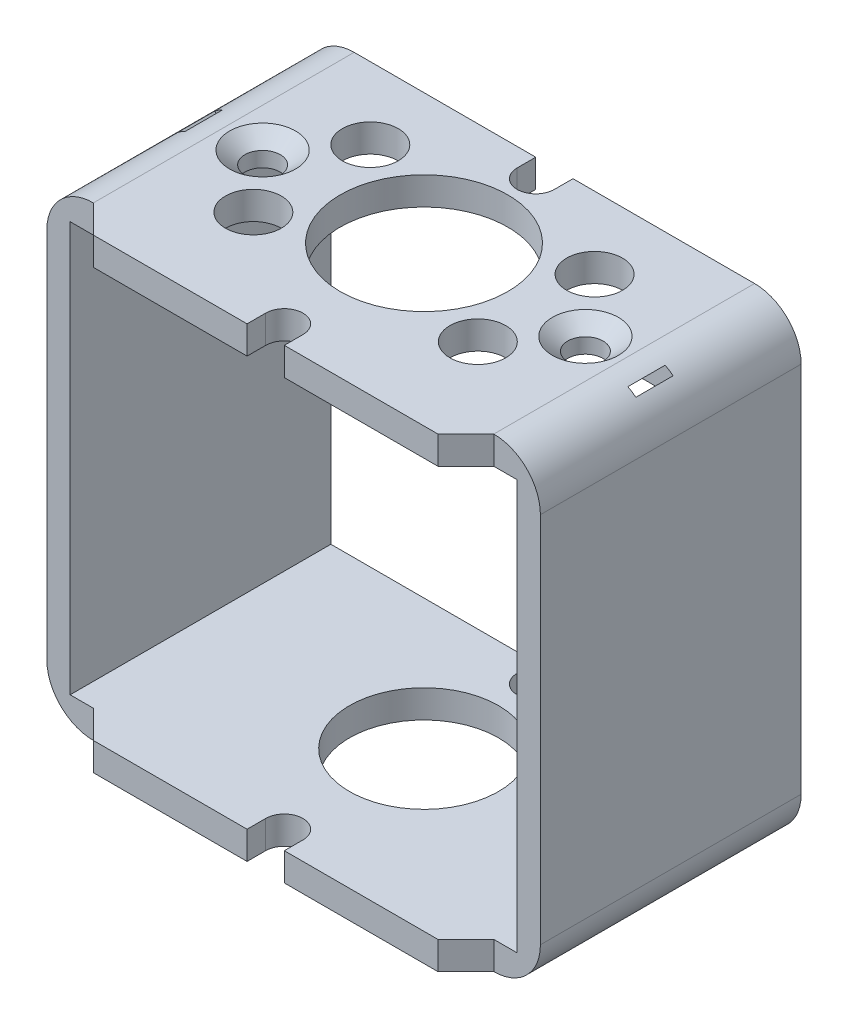
SolidWorks part; units mm, degrees
material "AISI 1020"
ref_plane "Front" through (0, 0, 0) normal (0, 0, 1) x (1, 0, 0)
ref_plane "Top" through (0, 0, 0) normal (0, 1, 0) x (1, 0, 0)
ref_plane "Right" through (0, 0, 0) normal (1, 0, 0) x (0, 0, -1)
sketch "Sketch1" plane through (0, 0, 0) normal (0, 0, 1) x (1, 0, 0)
  line L1 (-26.5, -25) -> (26.5, -25)
  line L2 (-26.5, -25) -> (-26.5, 25)
  line L3 (-26.5, 25) -> (26.5, 25)
  line L4 (26.5, -25) -> (26.5, 25)
  line L5 (-26.5, -25) -> (26.5, 25) construction
  line L6 (-26.5, 25) -> (26.5, -25) construction
  point P0 (0, 0)
  dimension "D1" = 53
  dimension "D2" = 50
extrude "Boss-Extrude1" add sketch "Sketch1" along normal blind 28
fillet "Fillet1" radius 5 4 edges at (-26.5, 25, 14) (26.5, 25, 14) (26.5, -25, 14) (-26.5, -25, 14)
sketch "Sketch2" plane through (0, 0, 28) normal (0, 0, 1) x (1, 0, 0)
  line L1 (-24, -22) -> (24, -22)
  line L2 (-24, -22) -> (-24, 22)
  line L3 (-24, 22) -> (24, 22)
  line L4 (24, -22) -> (24, 22)
  line L5 (-24, -22) -> (24, 22) construction
  line L6 (-24, 22) -> (24, -22) construction
  point P0 (0, 0)
  dimension "D1" = 48
  dimension "D2" = 44
extrude "Cut-Extrude1" cut sketch "Sketch2" against normal blind 28
sketch "Sketch3" plane through (0, 0, 28) normal (0, 0, 1) x (1, 0, 0)
  line L0 (-21.5, -25) -> (-21.5, -22)
  line L1 (-24, -22) -> (24, -22) construction
  line L2 (-21.5, -22) -> (21.5, -22)
  line L3 (21.5, -22) -> (21.5, -25)
  line L4 (-21.5, -25) -> (21.5, -25) construction
  line L5 (21.5, -25) -> (-21.5, -25)
extrude "Boss-Extrude2" add sketch "Sketch3" along normal blind 3
sketch "Sketch9" plane through (0, -25, 0) normal (0, -1, 0) x (1, 0, 0)
  line L0 (21.5, 28) -> (18.5, 31)
  line L1 (-21.5, 31) -> (21.5, 31) construction
  line L2 (18.5, 31) -> (21.5, 31)
  line L3 (21.5, 31) -> (21.5, 28)
extrude "Cut-Extrude2" cut sketch "Sketch9" against normal blind 3
mirror "Mirror1" about plane through (0, 0, 0) normal (1, 0, 0) of "Cut-Extrude2"
sketch "Sketch10" plane through (0, -25, 0) normal (0, -1, 0) x (-1, 0, 0)
  circle A0 centre (0, -14) radius 8
extrude "Cut-Extrude3" cut sketch "Sketch10" against normal blind 3
sketch "Sketch11" plane through (0, -25, 0) normal (0, -1, 0) x (1, 0, 0)
  line L0 (0, 31) -> (0, 29) construction
  line L1 (-18.5, 31) -> (18.5, 31) construction
  line L2 (2, 31) -> (2, 29)
  line L3 (-2, 31) -> (-2, 29)
  arc A0 (2, 31) -> (-2, 31) centre (0, 31) ccw
  arc A1 (-2, 29) -> (2, 29) centre (0, 29) ccw
  point P4 (0, 30)
  dimension "D1" = 2
  dimension "D2" = 4
extrude "Cut-Extrude4" cut sketch "Sketch11" against normal blind 3
sketch "Sketch12" plane through (0, -25, 0) normal (0, -1, 0) x (1, 0, 0)
  line L0 (0, 0) -> (0, 2) construction
  line L1 (-21.5, 0) -> (21.5, 0) construction
  line L2 (-2, 0) -> (-2, 2)
  line L3 (2, 0) -> (2, 2)
  arc A0 (-2, 0) -> (2, 0) centre (0, 0) ccw
  arc A1 (2, 2) -> (-2, 2) centre (0, 2) ccw
  point P4 (0, 1)
  dimension "D1" = 2
extrude "Cut-Extrude5" cut sketch "Sketch12" against normal blind 3
mirror "Mirror2" about plane through (0, 0, 0) normal (0, 1, 0) of "Cut-Extrude5", "Cut-Extrude2", "Cut-Extrude4", "Mirror1", "Boss-Extrude2"
sketch "Sketch13" plane through (0, 25, 0) normal (0, 1, 0) x (1, 0, 0)
  circle A0 centre (0, -14) radius 9
extrude "Cut-Extrude12" cut sketch "Sketch13" against normal blind 3
sketch "Sketch14" plane through (0, 25, 0) normal (0, 1, 0) x (1, 0, 0)
  circle A0 centre (-12.0525, -20.2708) radius 3
  dimension "D1" = 12.2064
extrude "Cut-Extrude13" cut sketch "Sketch14" against normal blind 3
sketch "Sketch15" plane through (0, 25, 0) normal (0, 1, 0) x (1, 0, 0)
  circle A0 centre (-12.0432, -7.7237) radius 3
  dimension "D1" = 12.2101
extrude "Cut-Extrude14" cut sketch "Sketch15" against normal blind 3
ref_plane "Plane8" through (-24.2855, 24.2855, 0) normal (-0.7071, 0.7071, 0) x (0, 0, -1)
sketch "Sketch39" plane through (-24.2855, 24.2855, 0) normal (-0.7071, 0.7071, 0) x (0, 0, -1)
  line L1 (-15.8649, -0.5) -> (-11.8649, -0.5)
  line L2 (-15.8649, -0.5) -> (-15.8649, 0.5)
  line L3 (-15.8649, 0.5) -> (-11.8649, 0.5)
  line L4 (-11.8649, -0.5) -> (-11.8649, 0.5)
  line L5 (-15.8649, -0.5) -> (-11.8649, 0.5) construction
  line L6 (-15.8649, 0.5) -> (-11.8649, -0.5) construction
  point P0 (-13.8649, 0)
  dimension "D1" = 4
  dimension "D2" = 1
extrude "Cut-Extrude15" cut sketch "Sketch39" against normal blind 5
hole_wizard "CSK for #6 Flat Head Machine Screw (100)1" positions "Sketch45" profile "Sketch46" countersink size "#6" standard "ANSI Inch"
sketch "Sketch45" plane through (0, 25, 0) normal (0, 1, 0) x (1, 0, 0)
  point P0 (-17.3324, -14)
sketch "Sketch46" plane through (-17.3324, 25, 14) normal (1, 0, 0) x (0, 0, 1)
  line L0 (0, 0) -> (0, 3)
  line L1 (0, 3) -> (1.8986, 3)
  line L2 (1.8986, 3) -> (1.8986, 1.38)
  line L3 (1.8986, 1.38) -> (3.5433, 0)
  line L5 (3.5433, 0) -> (0, 0)
  line L6 (-1.8986, 1.38) -> (-3.5433, 0) construction
  line L11 (0, -6.35) -> (0, 107.95) construction
  dimension "Thru Hole Dia." = 3.7973
  dimension "Thru Hole Depth" = 3
  dimension "Near C'Sink Dia." = 7.0866
  dimension "Near C'Sink Angle" = 100
mirror "Mirror3" about plane through (0, 0, 0) normal (1, 0, 0) of "Cut-Extrude15", "Cut-Extrude14", "CSK for #6 Flat Head Machine Screw (100)1", "Cut-Extrude13"
